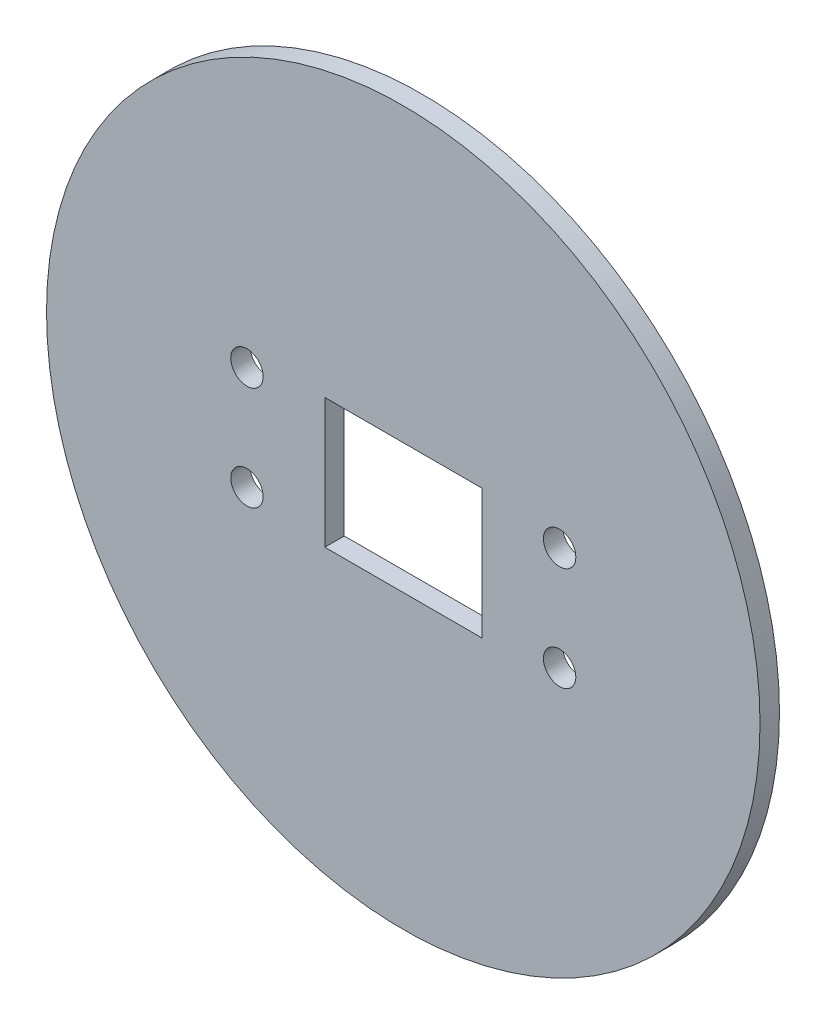
SolidWorks part; units mm, degrees
ref_plane "前视基准面" through (0, 0, 0) normal (0, 0, 1) x (1, 0, 0)
ref_plane "上视基准面" through (0, 0, 0) normal (0, 1, 0) x (1, 0, 0)
ref_plane "右视基准面" through (0, 0, 0) normal (1, 0, 0) x (0, 0, -1)
sketch "草图2" plane through (0, 0, 0) normal (0, 0, 1) x (1, 0, 0)
  line L1 (-6.05, 5) -> (6.05, 5)
  line L2 (-6.05, 5) -> (-6.05, -5)
  line L3 (-6.05, -5) -> (6.05, -5)
  line L4 (6.05, 5) -> (6.05, -5)
  line L5 (-6.05, 5) -> (6.05, -5) construction
  line L6 (-6.05, -5) -> (6.05, 5) construction
  circle A0 centre (0, 0) radius 27.5
  dimension "D1" = 55
  dimension "D2" = 10
  dimension "D3" = 12.1
extrude "凸台-拉伸2" add sketch "草图2" along normal blind 1.5 contours L2 L3 L4 L1 | A0
sketch "草图3" plane through (0, 0, 1.5) normal (0, 0, 1) x (1, 0, 0)
  line L0 (6.05, 5) -> (6.05, -5) construction
  line L2 (0.825, 0) -> (-0.825, 0) construction
  line L3 (0, -0.825) -> (0, 0.825) construction
  circle A0 centre (12.05, 4) radius 1.25
  circle A1 centre (-12.05, 4) radius 1.25
  circle A2 centre (12.05, -4) radius 1.25
  circle A3 centre (-12.05, -4) radius 1.25
  dimension "D1" = 6
  dimension "D2" = 4
extrude "切除-拉伸1" cut sketch "草图3" against normal blind 10
